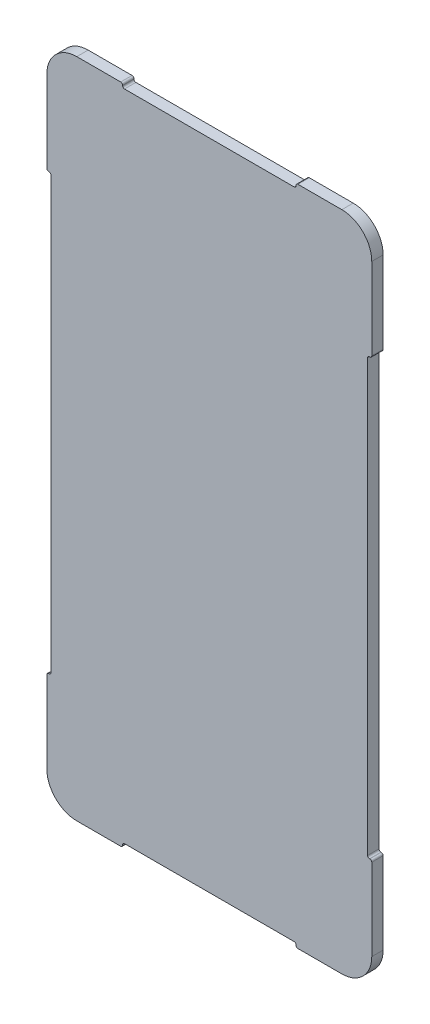
SolidWorks part; units mm, degrees
ref_plane "Front" through (0, 0, 0) normal (0, 0, 1) x (1, 0, 0)
ref_plane "Top" through (0, 0, 0) normal (0, 1, 0) x (1, 0, 0)
ref_plane "Right" through (0, 0, 0) normal (1, 0, 0) x (0, 0, -1)
ref_plane "Plane1" through (0, 0, 3) normal (0, 0, 1) x (1, 0, 0)
sketch "Sketch1" plane through (0, 0, 3) normal (0, 0, 1) x (1, 0, 0)
  line L0 (42.4, 57.4) -> (42.3, 57.4)
  line L1 (42.9, 79.5) -> (42.9, 57.9)
  line L2 (22.4, 86.3) -> (-22.4, 86.3)
  line L3 (-22.9, 86.8) -> (-22.9, 86.9)
  line L4 (-23.4, 87.4) -> (-35, 87.4)
  line L5 (-42.9, 79.5) -> (-42.9, 57.9)
  line L6 (-42.4, 57.4) -> (-42.3, 57.4)
  line L7 (-41.8, 56.9) -> (-41.8, -56.9)
  line L8 (23.4, 87.4) -> (35, 87.4)
  line L9 (22.9, 86.8) -> (22.9, 86.9)
  line L10 (41.8, 56.9) -> (41.8, -56.9)
  line L11 (22.9, -86.8) -> (22.9, -86.9)
  line L12 (23.4, -87.4) -> (35, -87.4)
  line L13 (-42.4, -57.4) -> (-42.3, -57.4)
  line L14 (-42.9, -79.5) -> (-42.9, -57.9)
  line L15 (-23.4, -87.4) -> (-35, -87.4)
  line L16 (-22.9, -86.8) -> (-22.9, -86.9)
  line L17 (22.4, -86.3) -> (-22.4, -86.3)
  line L18 (42.9, -79.5) -> (42.9, -57.9)
  line L19 (42.4, -57.4) -> (42.3, -57.4)
  line L20 (0, 79.5) -> (0, 0) construction
  line L21 (0, 0) -> (66.3647, 0) construction
  arc A0 (42.3, 57.4) -> (41.8, 56.9) centre (42.3, 56.9) ccw
  arc A1 (42.9, 57.9) -> (42.4, 57.4) centre (42.4, 57.9) cw
  arc A2 (35, 87.4) -> (42.9, 79.5) centre (35, 79.5) cw
  arc A3 (-22.4, 86.3) -> (-22.9, 86.8) centre (-22.4, 86.8) cw
  arc A4 (-22.9, 86.9) -> (-23.4, 87.4) centre (-23.4, 86.9) ccw
  arc A5 (-35, 87.4) -> (-42.9, 79.5) centre (-35, 79.5) ccw
  arc A6 (-42.9, 57.9) -> (-42.4, 57.4) centre (-42.4, 57.9) ccw
  arc A7 (-42.3, 57.4) -> (-41.8, 56.9) centre (-42.3, 56.9) cw
  arc A8 (22.9, 86.9) -> (23.4, 87.4) centre (23.4, 86.9) cw
  arc A9 (22.4, 86.3) -> (22.9, 86.8) centre (22.4, 86.8) ccw
  arc A10 (22.4, -86.3) -> (22.9, -86.8) centre (22.4, -86.8) cw
  arc A11 (22.9, -86.9) -> (23.4, -87.4) centre (23.4, -86.9) ccw
  arc A12 (-42.3, -57.4) -> (-41.8, -56.9) centre (-42.3, -56.9) ccw
  arc A13 (-42.9, -57.9) -> (-42.4, -57.4) centre (-42.4, -57.9) cw
  arc A14 (-35, -87.4) -> (-42.9, -79.5) centre (-35, -79.5) cw
  arc A15 (-22.9, -86.9) -> (-23.4, -87.4) centre (-23.4, -86.9) cw
  arc A16 (-22.4, -86.3) -> (-22.9, -86.8) centre (-22.4, -86.8) ccw
  arc A17 (35, -87.4) -> (42.9, -79.5) centre (35, -79.5) ccw
  arc A18 (42.9, -57.9) -> (42.4, -57.4) centre (42.4, -57.9) ccw
  arc A19 (42.3, -57.4) -> (41.8, -56.9) centre (42.3, -56.9) cw
  dimension "D3" = 7.9
  dimension "D7" = 0.5
  dimension "D1" = 85.8
  dimension "D2" = 174.8
  dimension "D4" = 1.1
  dimension "D5" = 1.1
  dimension "D6" = 45.8
  dimension "D8" = 114.8
extrude "Boss-Extrude1" add sketch "Sketch1" against normal blind 3
